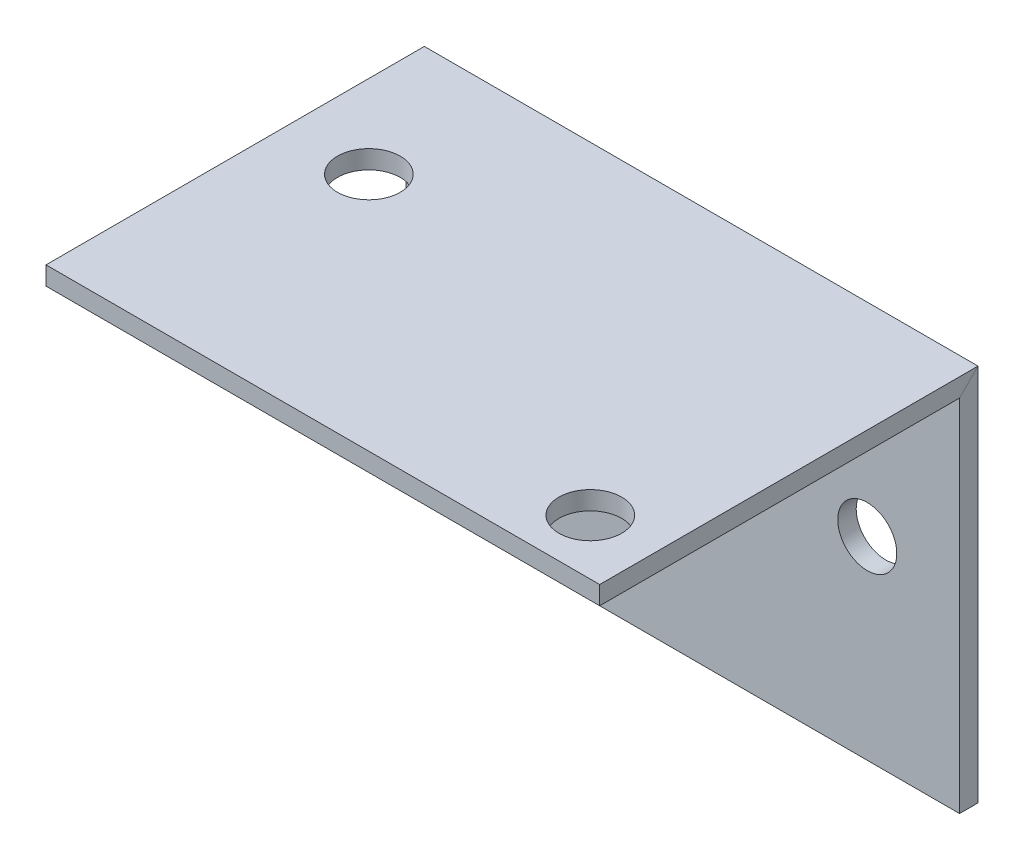
SolidWorks part; units mm, degrees
ref_plane "Plan de face" through (0, 0, 0) normal (0, 0, 1) x (1, 0, 0)
ref_plane "Plan de dessus" through (0, 0, 0) normal (0, 1, 0) x (1, 0, 0)
ref_plane "Plan de droite" through (0, 0, 0) normal (1, 0, 0) x (0, 0, -1)
sketch "Esquisse1" plane through (0, 0, 0) normal (0, 0, 1) x (1, 0, 0)
  line L1 (-15, 0.5) -> (15, 0.5)
  line L2 (-15, 0.5) -> (-15, -0.5)
  line L3 (-15, -0.5) -> (15, -0.5)
  line L4 (15, 0.5) -> (15, -0.5)
  line L5 (-15, 0.5) -> (15, -0.5) construction
  line L6 (-15, -0.5) -> (15, 0.5) construction
  point P0 (0, 0)
  dimension "D1" = 30
  dimension "D2" = 1
sketch "Esquisse6" plane through (0, 0, 0) normal (1, 0, 0) x (0, 0, -1)
  line L0 (0, 0) -> (20, 0)
  line L1 (0, -0.5) -> (0, 0.5) construction
  line L2 (20, 0) -> (20, -20)
  dimension "D1" = 20
  dimension "D2" = 20
sweep "Balayage1" add profiles "Esquisse1" path "Esquisse6"
sketch "Esquisse7" plane through (0, -0.5, 0) normal (0, -1, 0) x (1, 0, 0)
  circle A0 centre (11.4934, -3) radius 1.7 construction
  circle A1 centre (11.4934, -3) radius 1.7
  circle A2 centre (-10.5066, -13) radius 1.7 construction
  circle A3 centre (-10.5066, -13) radius 1.7
extrude "Enlèv. mat.-Extru.1" cut sketch "Esquisse7" against normal through all
sketch "Esquisse8" plane through (0, 0, -19.5) normal (0, 0, 1) x (1, 0, 0)
  line L0 (0, -5.1336) -> (0, -13.1761) construction
  line L1 (-3.7428, -9.5) -> (4.7574, -9.5) construction
  line L2 (-15, -0.5) -> (15, -0.5) construction
  circle A0 centre (-10, -9.5) radius 1.6
  circle A1 centre (10, -9.5) radius 1.6
  point P9 (-8.8429, -9.5)
  point P10 (0, 0)
  dimension "D1" = 3.2
  dimension "D2" = 9
  dimension "D3" = 10
extrude "Enlèv. mat.-Extru.2" cut sketch "Esquisse8" against normal through all
